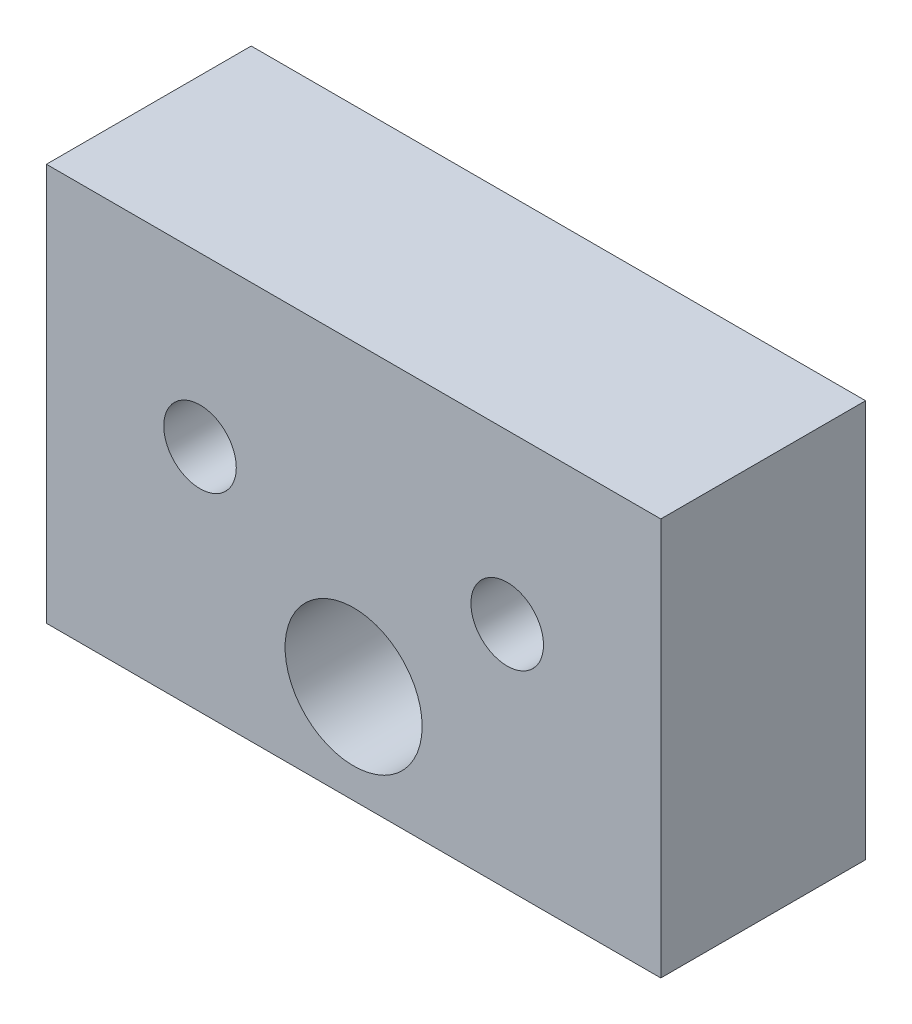
SolidWorks part; units mm, degrees
material "Acrylic (Medium-high impact)"
ref_plane "Front Plane" through (0, 0, 0) normal (0, 0, 1) x (1, 0, 0)
ref_plane "Top Plane" through (0, 0, 0) normal (0, 1, 0) x (1, 0, 0)
ref_plane "Right Plane" through (0, 0, 0) normal (1, 0, 0) x (0, 0, -1)
sketch "Sketch1" plane through (0, 0, 0) normal (0, 0, 1) x (1, 0, 0)
  line L2 (38.1, -12.224) -> (38.1, 12.224)
  line L4 (-38.1, -12.224) -> (-38.1, 12.224)
  line L8 (-38.1, -12.224) -> (38.1, -12.224)
  line L11 (-38.1, 37.084) -> (-38.1, 12.224)
  line L12 (38.1, 12.224) -> (38.1, 37.084)
  line L13 (-38.1, 37.084) -> (-38.1, 49.2259)
  line L14 (-38.1, 37.084) -> (38.1, 37.084)
  line L16 (-38.1, 49.2259) -> (38.1, 49.2259)
  line L18 (38.1, 37.084) -> (38.1, 49.2259)
  circle A0 centre (0, 0) radius 8.5
  circle A1 centre (19.05, 16.256) radius 4.5
  circle A2 centre (-19.05, 16.256) radius 4.5
  point P0 (0, 0)
  point P6 (-38.1, 0)
  dimension "D3" = 17
  dimension "D4" = 9
  dimension "D1" = 76.2
  dimension "D2" = 20.828
  dimension "D5" = 19.05
  dimension "D6" = 16.256
  dimension "D7" = 19.05
  dimension "D8" = 61.4499
  dimension "D9" = 76.2
extrude "Boss-Extrude1" add sketch "Sketch1" along normal mid plane 25.4 contours L14 L11 L4 L8 L2 L12 A2 A1 A0
